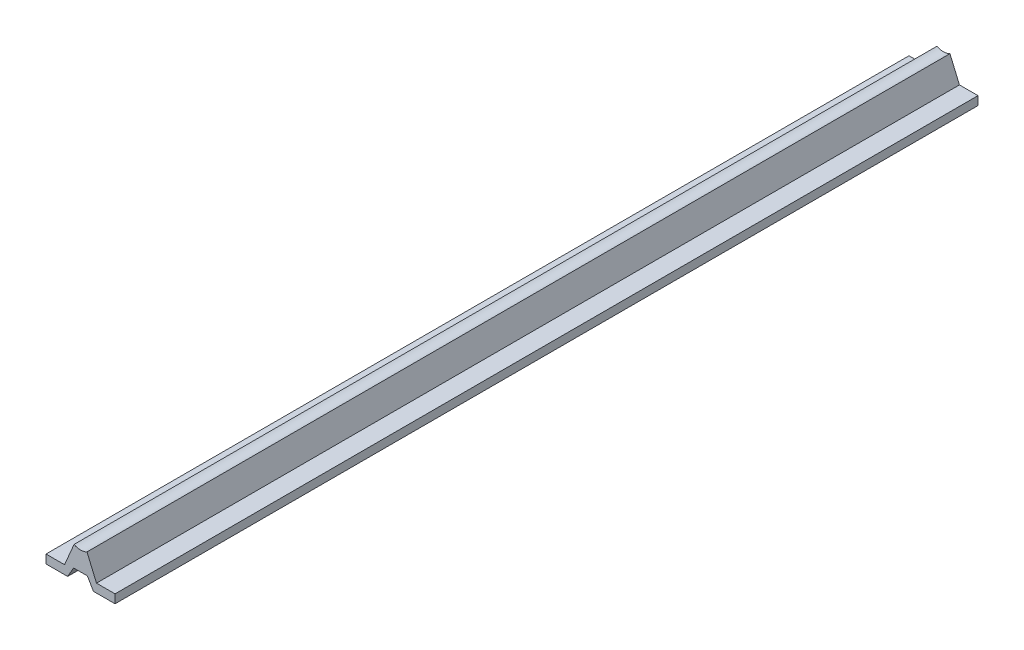
SolidWorks part; units mm, degrees
material "6063-T5"
ref_plane "Front Plane" through (0, 0, 0) normal (0, 0, 1) x (1, 0, 0)
ref_plane "Top Plane" through (0, 0, 0) normal (0, 1, 0) x (1, 0, 0)
ref_plane "Right Plane" through (0, 0, 0) normal (1, 0, 0) x (0, 0, -1)
sketch "Sketch1" plane through (0, 0, 0) normal (0, 0, 1) x (1, 0, 0)
  line L0 (-20, -25) -> (-7.4641, -25)
  line L1 (-7.4641, -25) -> (-4, -19)
  line L2 (-4, -19) -> (4, -19)
  line L3 (4, -19) -> (7.4641, -25)
  line L4 (7.4641, -25) -> (20, -25)
  line L5 (20, -25) -> (20, -20)
  line L6 (20, -20) -> (9.25, -20)
  line L10 (-20, -25) -> (-20, -20)
  line L11 (-20, -20) -> (-9.25, -20)
  line L15 (-9.25, -20) -> (-3.75, -7.0666)
  line L16 (0, -8) -> (0, 0) construction
  line L17 (3.75, -7.0666) -> (9.25, -20)
  line L18 (0, -8) -> (0, -19) construction
  arc A0 (-3.75, -7.0666) -> (3.75, -7.0666) centre (0, 0) ccw
  dimension "D1" = 8
  dimension "D2" = 7.5
  dimension "D3" = 5
  dimension "D4" = 25
  dimension "D5" = 18.5
  dimension "D7" = 20
  dimension "D10" = 8
  dimension "D11" = 60
  dimension "D12" = 6
  dimension "D13" = 40
extrude "Boss-Extrude1" add sketch "Sketch1" along normal blind 500
ref_plane "Плоскость1" through (0, 0, 0) normal (1, 0, 0) x (0, 0, -1)
equation "\"SBR16.Length.X\"= 600мм"
equation "\"SBR16.Length.Y\"= 500мм"
equation "\"SBR16.Length.Z\"= 250мм"
equation "\"D1@Boss-Extrude1\"= \"SBR16.Length.Y\""
